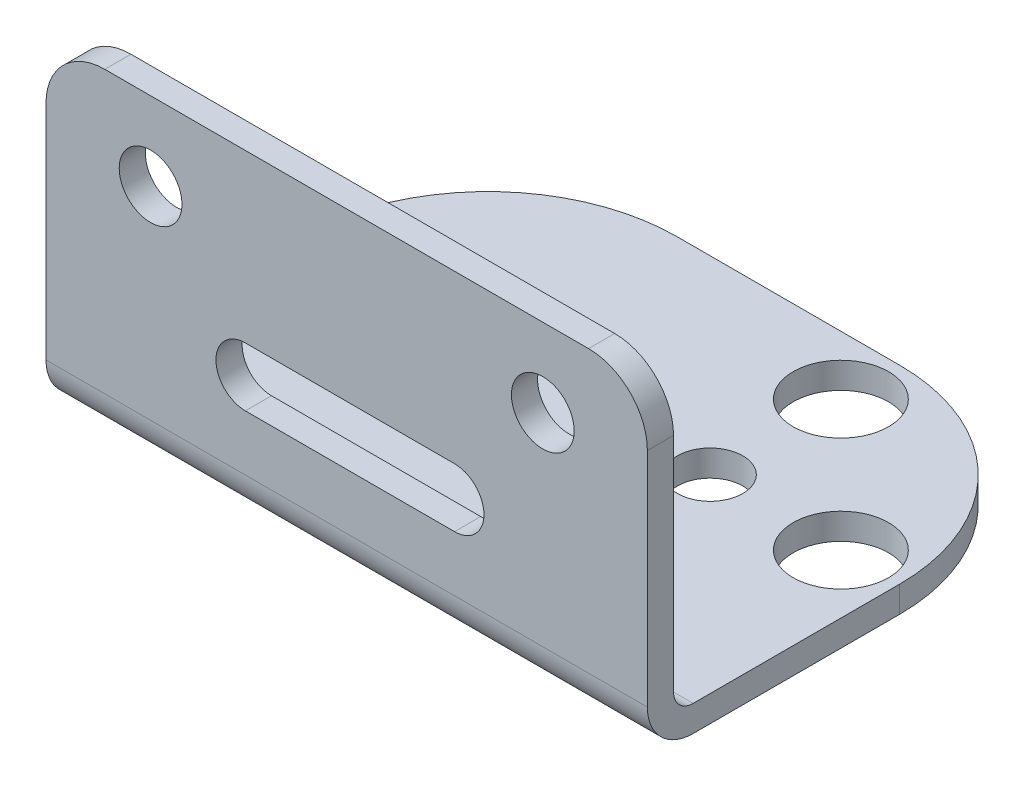
SolidWorks part; units mm, degrees
material "6061 合金"
ref_plane "前视基准面" through (0, 0, 0) normal (0, 0, 1) x (1, 0, 0)
ref_plane "上视基准面" through (0, 0, 0) normal (0, 1, 0) x (1, 0, 0)
ref_plane "右视基准面" through (0, 0, 0) normal (1, 0, 0) x (0, 0, -1)
other "Configuration Table"
sketch "草图3" plane through (0, 0, 0) normal (0, 1, 0) x (1, 0, 0)
  line L0 (0, 0) -> (46, 0)
  line L1 (46, 0) -> (46, 33.8)
  line L2 (46, 33.8) -> (0, 33.8)
  line L3 (0, 33.8) -> (0, 0)
  dimension "D1" = 33.8
  dimension "D2" = 46
extrude "凸台-拉伸1" add sketch "草图3" along normal blind 2
fillet "圆角1" radius 14.5 2 edges at (0, 1, -33.8) (46, 1, -33.8)
sketch "草图4" plane through (0, 2, 0) normal (0, 1, 0) x (1, 0, 0)
  line L0 (31.5, 33.8) -> (31.5, 0) construction
  line L1 (0, 0) -> (46, 0) construction
  line L2 (46, 19.3) -> (0, 19.3) construction
  circle A0 centre (31.5, 19.3) radius 2.5
  circle A1 centre (41.5, 19.3) radius 3.65
  circle A2 centre (31.5, 29.3) radius 3.65
  circle A3 centre (31.5, 9.3) radius 3.65
  circle A4 centre (11.5, 19.3) radius 3.65
  point P5 (46, 19.3)
  point P9 (31.5, 19.3)
  point P14 (46, 19.3)
  dimension "D1" = 5
  dimension "D2" = 7.3
  dimension "D4" = 7.3
  dimension "D5" = 7.3
  dimension "D8" = 7.3
  dimension "D3" = 10
  dimension "D6" = 10
  dimension "D7" = 10
  dimension "D9" = 20
extrude "切除-拉伸1" cut sketch "草图4" against normal blind 2
sketch "草图5" plane through (0, 0, 0) normal (0, -1, 0) x (1, 0, 0)
  line L0 (0, 0) -> (46, 0)
  line L1 (46, 0) -> (46, -2)
  line L2 (46, 0) -> (46, -19.3) construction
  line L3 (46, -2) -> (0, -2)
  line L4 (0, -2) -> (0, 0)
  dimension "D1" = 2
extrude "凸台-拉伸2" add sketch "草图5" against normal blind 25
fillet "圆角2" radius 4.5 2 edges at (0, 25, -1) (46, 25, -1)
fillet "圆角3" radius 3.5 1 edges at (23, 0, 0)
fillet "圆角4" radius 1.5 1 edges at (23, 2, -2)
sketch "草图6" plane through (0, 0, 0) normal (0, 0, 1) x (1, 0, 0)
  line L0 (41.5, 25) -> (4.5, 25) construction
  line L1 (46, 20.5) -> (46, 3.5) construction
  line L2 (0, 20.5) -> (0, 3.5) construction
  line L9 (15.25, 10) -> (31.25, 10) construction
  line L10 (15.25, 7.75) -> (31.25, 7.75)
  line L11 (15.25, 12.25) -> (31.25, 12.25)
  line L12 (0, 10) -> (46, 10) construction
  line L13 (0, 19) -> (46, 19) construction
  arc A4 (15.25, 7.75) -> (15.25, 12.25) centre (15.25, 10) cw
  arc A5 (31.25, 12.25) -> (31.25, 7.75) centre (31.25, 10) cw
  circle A6 centre (38, 19) radius 2.4
  circle A7 centre (8, 19) radius 2.4
  point P27 (23.25, 10)
  dimension "D2" = 6
  dimension "D3" = 8
  dimension "D1" = 4.8
  dimension "D4" = 4.8
  dimension "D10" = 2.25
  dimension "D5" = 8
  dimension "D6" = 6
  dimension "D7" = 15
  dimension "D8" = 23.25
  dimension "D9" = 16
extrude "切除-拉伸2" cut sketch "草图6" against normal blind 25
